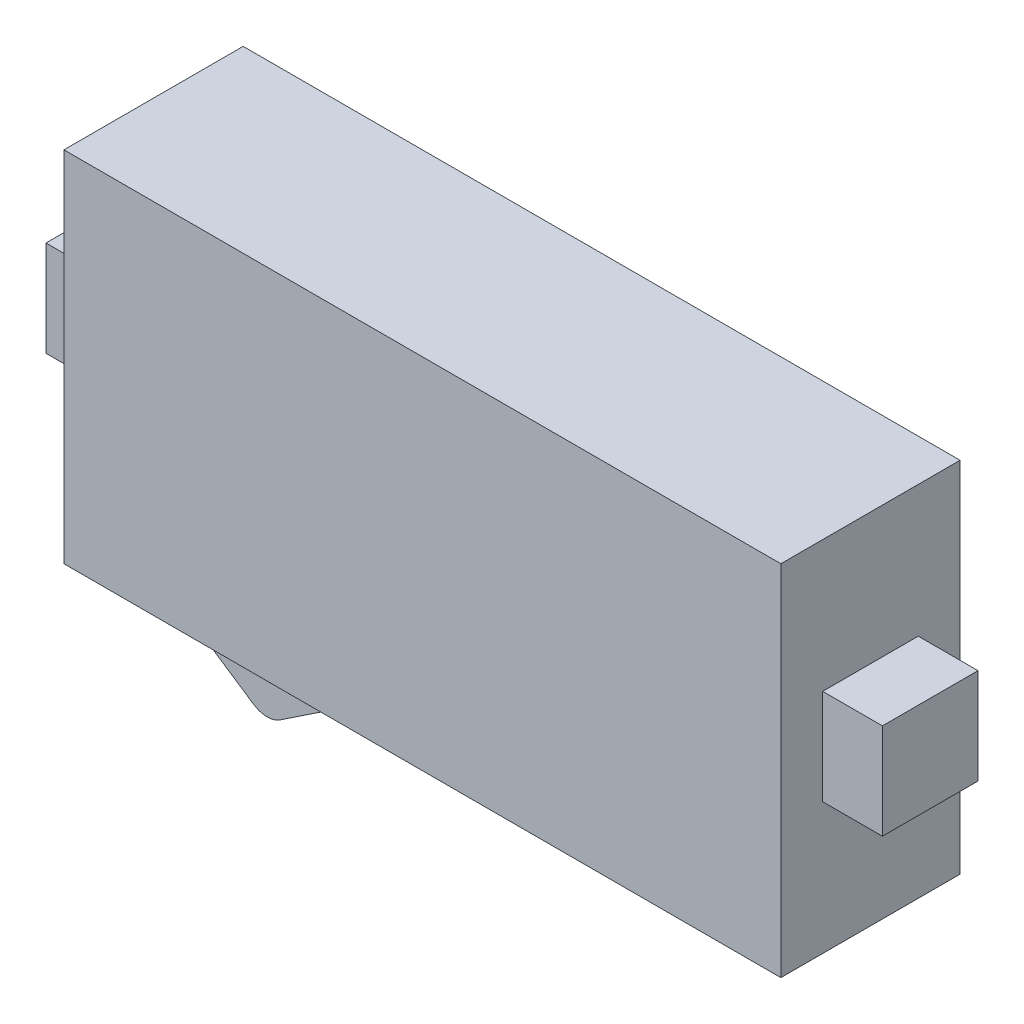
SolidWorks part; units mm, degrees
ref_plane "前视基准面" through (0, 0, 0) normal (0, 0, 1) x (1, 0, 0)
ref_plane "上视基准面" through (0, 0, 0) normal (0, 1, 0) x (1, 0, 0)
ref_plane "右视基准面" through (0, 0, 0) normal (1, 0, 0) x (0, 0, -1)
sketch "草图1" plane through (0, 0, 0) normal (0, 0, 1) x (1, 0, 0)
  line L1 (15, -7.5) -> (-15, -7.5)
  line L2 (15, -7.5) -> (15, 7.5)
  line L3 (15, 7.5) -> (-15, 7.5)
  line L4 (-15, -7.5) -> (-15, 7.5)
  line L5 (15, -7.5) -> (-15, 7.5) construction
  line L6 (15, 7.5) -> (-15, -7.5) construction
  point P0 (0, 0)
  dimension "D1" = 30
  dimension "D2" = 15
extrude "凸台-拉伸1" add sketch "草图1" along normal mid plane 7.5
sketch "草图2" plane through (-15, 0, 0) normal (-1, 0, 0) x (0, 0, 1)
  line L0 (-3.75, 0) -> (3.75, 0) construction
  line L1 (-3.75, 7.5) -> (-3.75, -7.5) construction
  line L2 (3.75, 7.5) -> (3.75, -7.5) construction
  line L3 (0, 7.5) -> (0, -7.5) construction
  line L4 (3.75, 7.5) -> (-3.75, 7.5) construction
  line L5 (3.75, -7.5) -> (-3.75, -7.5) construction
  line L7 (-2, 2) -> (2, 2)
  line L8 (-2, 2) -> (-2, -2)
  line L9 (-2, -2) -> (2, -2)
  line L10 (2, 2) -> (2, -2)
  line L11 (-2, 2) -> (2, -2) construction
  line L12 (-2, -2) -> (2, 2) construction
  point P12 (0, 0)
  dimension "D1" = 4
  dimension "D2" = 4
extrude "凸台-拉伸2" add sketch "草图2" along normal blind 2.5
mirror "镜向1" about plane through (0, 0, 0) normal (1, 0, 0) of "凸台-拉伸2"
sketch "草图4" plane through (0, 0, 0) normal (0, 0, 1) x (1, 0, 0)
  line L0 (-8, 7.5) -> (-8, -7.5) construction
  line L1 (15, 7.5) -> (-15, 7.5) construction
  line L2 (-15, -7.5) -> (15, -7.5) construction
  line L3 (-15, 7.5) -> (-15, -7.5) construction
  line L4 (-12.5, -7.5) -> (-8, -10.5)
  line L5 (-3.5, -7.5) -> (-8, -10.5)
  line L6 (-12.5, -7.5) -> (-3.5, -7.5)
  dimension "D1" = 7
  dimension "D2" = 3
  dimension "D3" = 9
extrude "凸台-拉伸3" add sketch "草图4" against normal mid plane 4.5
fillet "圆角1" radius 1 1 edges at (-8, -10.5, 0)
